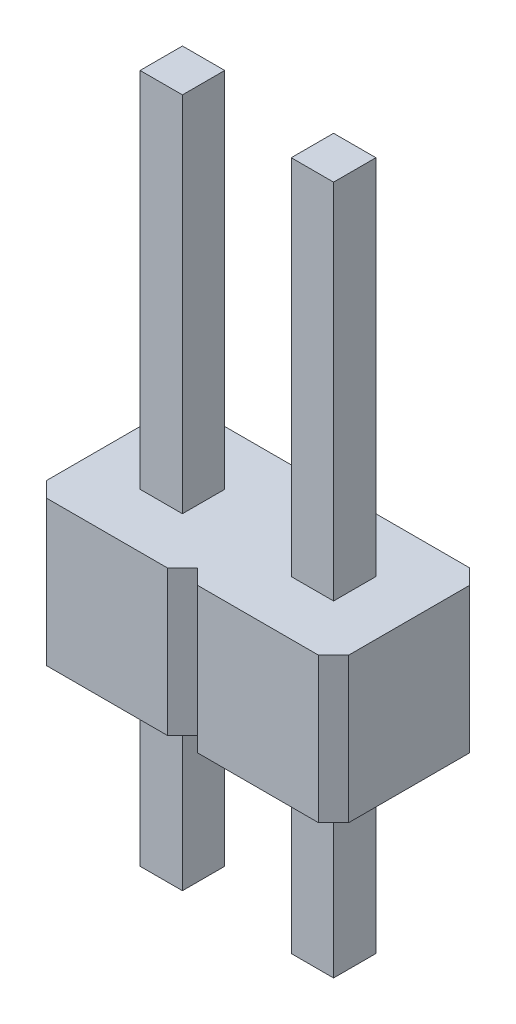
SolidWorks part; units mm, degrees
ref_plane "Alzado" through (0, 0, 0) normal (0, 0, 1) x (1, 0, 0)
ref_plane "Planta" through (0, 0, 0) normal (0, 1, 0) x (1, 0, 0)
ref_plane "Vista lateral" through (0, 0, 0) normal (1, 0, 0) x (0, 0, -1)
sketch "Croquis1" plane through (0, 0, 0) normal (0, 1, 0) x (1, 0, 0)
  line L0 (-2.5, 1.25) -> (-2.25, 1.25) construction
  line L1 (-2.25, 1.25) -> (-0.25, 1.25)
  line L2 (-2.5, 1) -> (-2.5, -1)
  line L3 (-2.25, -1.25) -> (-0.25, -1.25)
  line L4 (2.5, 1) -> (2.5, -1)
  line L5 (-2.5, 1.25) -> (2.5, -1.25) construction
  line L6 (-2.5, -1.25) -> (2.5, 1.25) construction
  line L7 (-2.25, 1.25) -> (-2.5, 1) construction
  line L8 (-2.5, 1) -> (-2.5, 1.25) construction
  line L9 (0, 0) -> (0, 1.25) construction
  line L10 (0, 0) -> (0, -1.25) construction
  line L11 (0, 1.25) -> (-0.25, 1.25) construction
  line L12 (-0.25, 1.25) -> (0, 1) construction
  line L13 (0, 1) -> (0.25, 1.25) construction
  line L14 (0.25, 1.25) -> (0, 1.25) construction
  line L15 (2.5, 1.25) -> (2.5, 1) construction
  line L16 (2.5, 1) -> (2.25, 1.25) construction
  line L17 (2.25, 1.25) -> (2.5, 1.25) construction
  line L18 (2.5, -1.25) -> (2.5, -1) construction
  line L19 (2.5, -1) -> (2.25, -1.25) construction
  line L20 (2.25, -1.25) -> (2.5, -1.25) construction
  line L21 (0, -1.25) -> (0.25, -1.25) construction
  line L22 (0.25, -1.25) -> (0, -1) construction
  line L23 (0, -1) -> (-0.25, -1.25) construction
  line L24 (-0.25, -1.25) -> (0, -1.25) construction
  line L25 (-2.5, -1.25) -> (-2.5, -1) construction
  line L26 (-2.5, -1) -> (-2.25, -1.25) construction
  line L27 (-2.25, -1.25) -> (-2.5, -1.25) construction
  line L28 (-2.5, -1) -> (-2.25, -1.25)
  line L29 (-0.25, -1.25) -> (0, -1)
  line L30 (0, -1) -> (0.25, -1.25)
  line L31 (2.25, -1.25) -> (2.5, -1)
  line L32 (2.5, 1) -> (2.25, 1.25)
  line L33 (-0.25, 1.25) -> (0, 1)
  line L34 (0, 1) -> (0.25, 1.25)
  line L35 (-2.5, 1) -> (-2.25, 1.25)
  line L36 (0.25, 1.25) -> (2.25, 1.25)
  line L37 (0.25, -1.25) -> (2.25, -1.25)
  point P0 (0, 0)
  dimension "D1" = 5
  dimension "D2" = 2.5
  dimension "D3" = 0.25
  dimension "D4" = 0.25
  dimension "D5" = 0.25
  dimension "D6" = 0.25
  dimension "D7" = 0.25
  dimension "D8" = 0.25
  dimension "D9" = 0.25
extrude "Saliente-Extruir1" add sketch "Croquis1" along normal blind 2.4
sketch "Croquis2" plane through (0, 2.4, 0) normal (0, 1, 0) x (1, 0, 0)
  line L0 (-1.25, 1.25) -> (-1.25, -1.25) construction
  line L1 (-0.25, 1.25) -> (-2.25, 1.25) construction
  line L2 (-2.25, -1.25) -> (-0.25, -1.25) construction
  line L3 (1.25, 1.25) -> (1.25, -1.25) construction
  line L4 (2.25, 1.25) -> (0.25, 1.25) construction
  line L5 (0.25, -1.25) -> (2.25, -1.25) construction
  line L6 (-2.5, 0) -> (2.5, 0) construction
  line L7 (-2.5, 1) -> (-2.5, -1) construction
  line L8 (2.5, -1) -> (2.5, 1) construction
  line L10 (-1.6, 0.35) -> (-0.9, 0.35)
  line L11 (-1.6, 0.35) -> (-1.6, -0.35)
  line L12 (-1.6, -0.35) -> (-0.9, -0.35)
  line L13 (-0.9, 0.35) -> (-0.9, -0.35)
  line L14 (-1.6, 0.35) -> (-0.9, -0.35) construction
  line L15 (-1.6, -0.35) -> (-0.9, 0.35) construction
  line L16 (0.9, 0.35) -> (1.6, 0.35)
  line L17 (0.9, 0.35) -> (0.9, -0.35)
  line L18 (0.9, -0.35) -> (1.6, -0.35)
  line L19 (1.6, 0.35) -> (1.6, -0.35)
  line L20 (0.9, 0.35) -> (1.6, -0.35) construction
  line L21 (0.9, -0.35) -> (1.6, 0.35) construction
  point P20 (-1.25, 0)
  point P25 (1.25, 0)
  dimension "D1" = 0.7
  dimension "D2" = 0.7
  dimension "D3" = 0.7
  dimension "D4" = 0.7
extrude "Saliente-Extruir2" add sketch "Croquis2" along normal blind 6
sketch "Croquis3" plane through (0, 0, 0) normal (0, -1, 0) x (1, 0, 0)
  line L0 (-2.5, 0) -> (2.5, 0) construction
  line L1 (-2.5, -1) -> (-2.5, 1) construction
  line L2 (2.5, 1) -> (2.5, -1) construction
  line L3 (-1.25, 1.25) -> (-1.25, -1.25) construction
  line L4 (-2.25, 1.25) -> (-0.25, 1.25) construction
  line L5 (-0.25, -1.25) -> (-2.25, -1.25) construction
  line L6 (1.25, 1.25) -> (1.25, -1.25) construction
  line L7 (0.25, 1.25) -> (2.25, 1.25) construction
  line L8 (2.25, -1.25) -> (0.25, -1.25) construction
  line L10 (-1.6, 0.35) -> (-0.9, 0.35)
  line L11 (-1.6, 0.35) -> (-1.6, -0.35)
  line L12 (-1.6, -0.35) -> (-0.9, -0.35)
  line L13 (-0.9, 0.35) -> (-0.9, -0.35)
  line L14 (-1.6, 0.35) -> (-0.9, -0.35) construction
  line L15 (-1.6, -0.35) -> (-0.9, 0.35) construction
  line L16 (1.6, -0.35) -> (0.9, -0.35)
  line L17 (1.6, -0.35) -> (1.6, 0.35)
  line L18 (1.6, 0.35) -> (0.9, 0.35)
  line L19 (0.9, -0.35) -> (0.9, 0.35)
  line L20 (1.6, -0.35) -> (0.9, 0.35) construction
  line L21 (1.6, 0.35) -> (0.9, -0.35) construction
  point P18 (-1.25, 0)
  point P23 (1.25, 0)
  dimension "D1" = 0.7
  dimension "D2" = 0.7
  dimension "D3" = 0.7
  dimension "D4" = 0.7
extrude "Saliente-Extruir3" add sketch "Croquis3" along normal blind 3 and the other way blind 2
